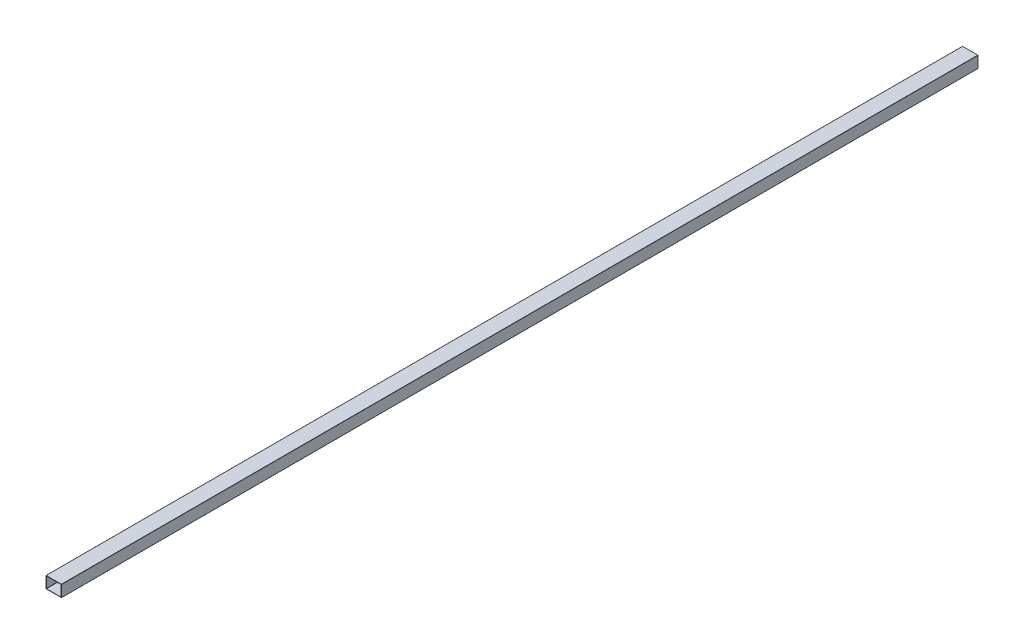
SolidWorks part; units mm, degrees
material "AISI 1035 Acero (SS)"
ref_plane "Alzado" through (0, 0, 0) normal (0, 0, 1) x (1, 0, 0)
ref_plane "Planta" through (0, 0, 0) normal (0, 1, 0) x (1, 0, 0)
ref_plane "Vista lateral" through (0, 0, 0) normal (1, 0, 0) x (0, 0, -1)
sketch "Croquis1" plane through (0, 0, 0) normal (0, 0, 1) x (1, 0, 0)
  line L0 (-48.91, -36.21) -> (-48.91, 36.21)
  line L1 (-50.8, -38.1) -> (50.8, -38.1)
  line L2 (-50.8, -38.1) -> (-50.8, 38.1)
  line L3 (-50.8, 38.1) -> (50.8, 38.1)
  line L4 (50.8, -38.1) -> (50.8, 38.1)
  line L5 (-50.8, -38.1) -> (50.8, 38.1) construction
  line L6 (-50.8, 38.1) -> (50.8, -38.1) construction
  line L7 (-48.91, 36.21) -> (48.91, 36.21)
  line L8 (48.91, -36.21) -> (48.91, 36.21)
  line L9 (-48.91, -36.21) -> (48.91, -36.21)
  point P0 (0, 0)
  dimension "D1" = 76.2
  dimension "D2" = 101.6
  dimension "D3" = 1.89
extrude "Saliente-Extruir1" add sketch "Croquis1" against normal blind 6000
fillet "Redondeo1" radius 1 8 edges at (-48.91, 36.21, -3000) (48.91, 36.21, -3000) (48.91, -36.21, -3000) (-50.8, -38.1, -3000) (-50.8, 38.1, -3000) (-48.91, -36.21, -3000) (50.8, -38.1, -3000) (50.8, 38.1, -3000)
